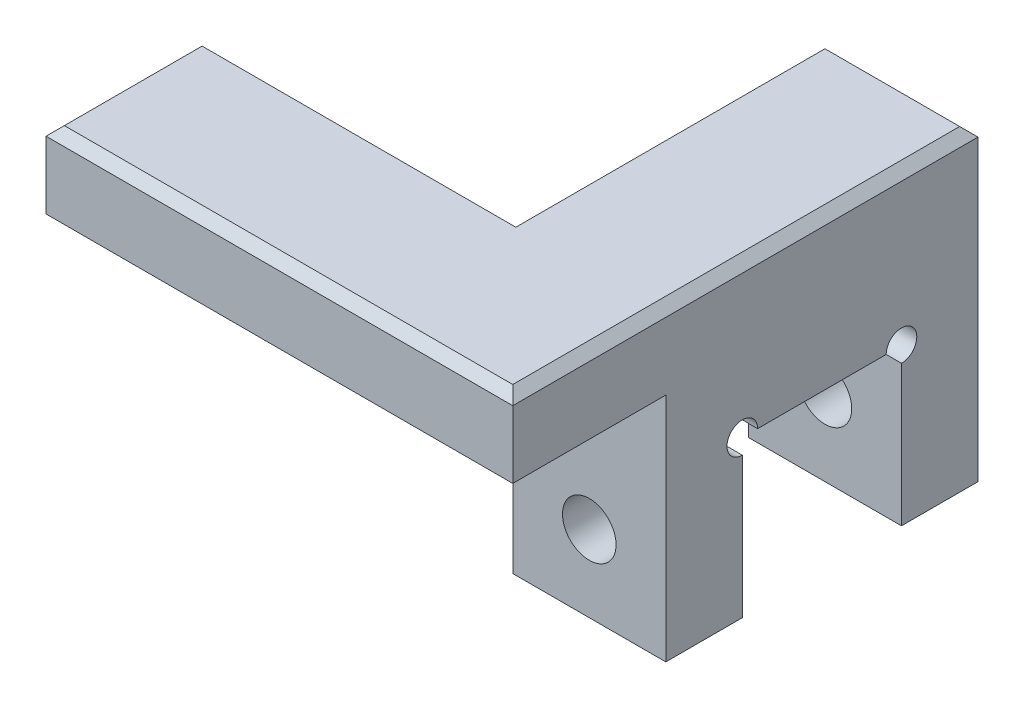
SolidWorks part; units mm, degrees
material "ﾎﾟﾘｴｽﾃﾙ樹脂"
ref_plane "正面" through (0, 0, 0) normal (0, 0, 1) x (1, 0, 0)
ref_plane "平面" through (0, 0, 0) normal (0, 1, 0) x (1, 0, 0)
ref_plane "右側面" through (0, 0, 0) normal (1, 0, 0) x (0, 0, -1)
sketch "ｽｹｯﾁ1" plane through (0, 0, 0) normal (1, 0, 0) x (0, 0, -1)
  line L0 (5.2, -5.1) -> (10.2, -5.1)
  line L1 (-5, -5) -> (5, -5) construction
  line L2 (-5, -5) -> (-5, 5) construction
  line L3 (-5, 5) -> (5, 5) construction
  line L4 (5, -5) -> (5, 5) construction
  line L5 (-5, -5) -> (5, 5) construction
  line L6 (-5, 5) -> (5, -5) construction
  line L7 (-5.2, -5.1) -> (5.2, -5.1)
  line L8 (-5.2, -5.1) -> (-5.2, 5.1)
  line L9 (-5.2, 5.1) -> (5.2, 5.1)
  line L10 (5.2, -5.1) -> (5.2, 5.1)
  line L11 (-5.2, -5.1) -> (5.2, 5.1) construction
  line L12 (-5.2, 5.1) -> (5.2, -5.1) construction
  line L13 (10.2, -5.1) -> (10.2, 10)
  line L14 (10.2, 10) -> (-10.2, 10)
  line L15 (-10.2, 10) -> (-10.2, -5.1)
  line L16 (-10.2, -5.1) -> (-5.2, -5.1)
  point P0 (0, 0)
  point P6 (0, 0)
  dimension "D1" = 10
  dimension "D2" = 10.4
  dimension "D3" = 10.2
  dimension "D4" = 5
  dimension "D5" = 5
extrude "ﾎﾞｽ - 押し出し1" add sketch "ｽｹｯﾁ1" along normal blind 10 contours L15 L16 L8 L9 L10 L0 L13 L14
sketch "ｽｹｯﾁ2" plane through (0, 0, 10.2) normal (0, 0, 1) x (1, 0, 0)
  line L0 (5, -5.1) -> (5, 10) construction
  line L1 (10, -5.1) -> (0, -5.1) construction
  line L2 (10, 10) -> (0, 10) construction
  circle A0 centre (5, -0.1) radius 1.75
  dimension "D1" = 5
  dimension "D2" = 3.5
extrude "ｶｯﾄ - 押し出し1" cut sketch "ｽｹｯﾁ2" against normal through all and the other way through all
sketch "ｽｹｯﾁ3" plane through (0, 10, 0) normal (0, 1, 0) x (1, 0, 0)
  line L0 (10, -10.2) -> (10, -20.2)
  line L1 (10, -20.2) -> (-20.5, -20.2)
  line L2 (-20.5, -20.2) -> (-20.5, -10)
  line L3 (-20.5, -10) -> (0, -10)
  line L4 (0, 10.2) -> (0, -10.2) construction
  line L5 (10, -10.2) -> (0, -10.2) construction
  line L6 (0, -10) -> (0, 10.2)
  line L7 (0, 10.2) -> (10, 10.2)
  line L8 (10, 10.2) -> (10, -10.2)
  dimension "D1" = 0.2
  dimension "D2" = 20.5
  dimension "D3" = 10
extrude "ﾎﾞｽ - 押し出し2" add sketch "ｽｹｯﾁ3" along normal blind 5
sketch "ｽｹｯﾁ4" plane through (0, 10, 0) normal (0, -1, 0) x (1, 0, 0)
  line L0 (-20.5, 15.1) -> (0, 15.1) construction
  line L1 (-20.5, 10) -> (-20.5, 20.2) construction
  circle A0 centre (-10.25, 15.1) radius 3.2
  dimension "D1" = 6.4
  dimension "D2" = 10.25
extrude "ｶｯﾄ - 押し出し2" cut sketch "ｽｹｯﾁ4" against normal blind 2.6
sketch "ｽｹｯﾁ5" plane through (0, 0, 0) normal (-1, 0, 0) x (0, 0, 1)
  circle A0 centre (5.2, 5.1) radius 1
  circle A1 centre (-5.2, 5.1) radius 1
  dimension "D1" = 2
extrude "ｶｯﾄ - 押し出し3" cut sketch "ｽｹｯﾁ5" against normal through all
fillet "ﾌｨﾚｯﾄ1" [suppressed] radius 3
fillet "ﾌｨﾚｯﾄ2" [suppressed] radius 3
chamfer "面取り1" distance 0.6 angle 45 6 edges at (-20.5, 15, 15.1) (-10.25, 15, 10) (0, 15, -0.1) (5, 15, -10.2) (10, 15, 5) (-5.25, 15, 20.2)
mirror "ﾐﾗｰ10" [suppressed]
sketch "ｽｹｯﾁ6" [suppressed] plane through (0, 15, 0) normal (0, 1, 0) x (1, 0, 0)
  line L1 (10, -20.2) -> (-35.2359, -20.2)
  line L2 (10, -20.2) -> (10, 17.5153)
  line L3 (10, 17.5153) -> (-35.2359, 17.5153)
  line L4 (-35.2359, -20.2) -> (-35.2359, 17.5153)
extrude "ｶｯﾄ - 押し出し4" [suppressed] cut sketch "ｽｹｯﾁ6" against normal through all
